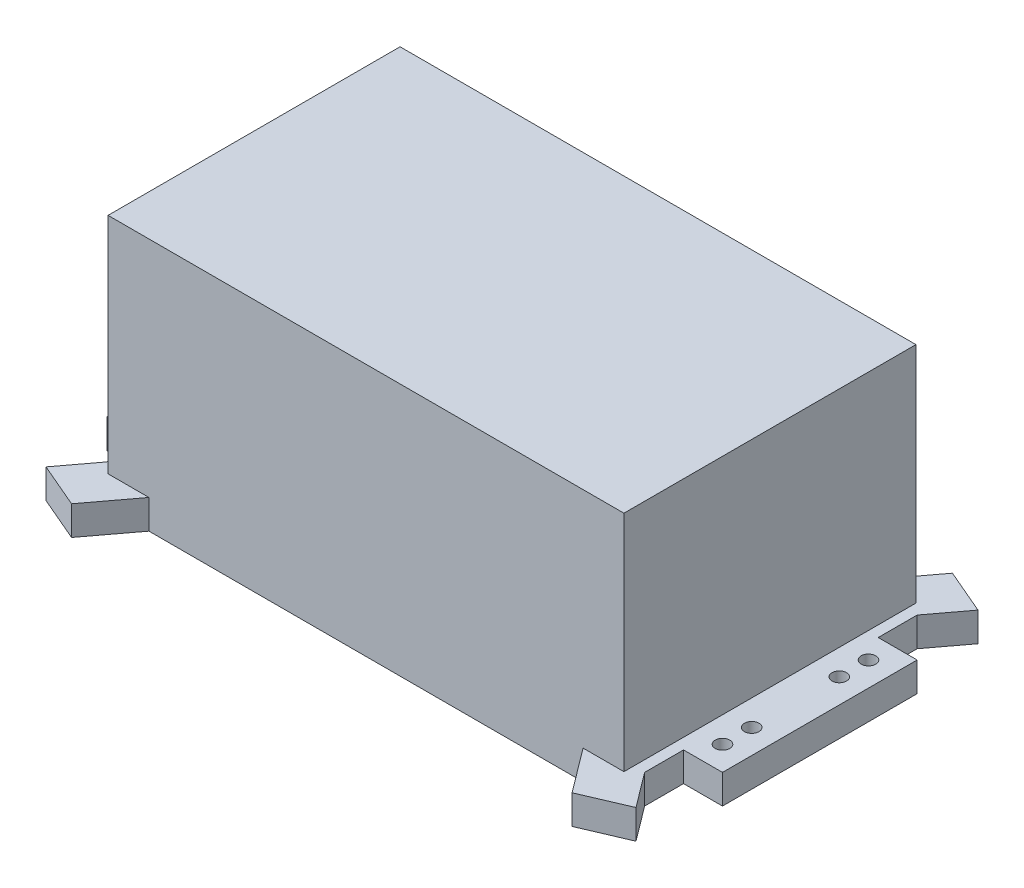
SolidWorks part; units mm, degrees
ref_plane "前视基准面" through (0, 0, 0) normal (0, 0, 1) x (1, 0, 0)
ref_plane "上视基准面" through (0, 0, 0) normal (0, 1, 0) x (1, 0, 0)
ref_plane "右视基准面" through (0, 0, 0) normal (1, 0, 0) x (0, 0, -1)
sketch "草图1" plane through (0, 0, 0) normal (0, 1, 0) x (1, 0, 0)
  line L0 (-65.7171, 0) -> (87.7991, 0) construction
  line L1 (44.6018, -30) -> (-44.6018, -30)
  line L3 (44.6018, 30) -> (-44.6018, 30)
  line L5 (53, -30) -> (-53, 30) construction
  line L6 (53, 30) -> (-53, -30) construction
  line L8 (63.25, -20) -> (63.25, 20)
  line L10 (-63.25, -20) -> (-63.25, 20)
  line L11 (63.25, 20) -> (55.25, 20)
  line L12 (55.25, 20) -> (55.25, 28)
  line L13 (55.25, 28) -> (60.6154, 35.1388)
  line L14 (60.6154, 35.1388) -> (51.4231, 39.0759)
  line L15 (51.4231, 39.0759) -> (44.6018, 30)
  line L16 (63.25, -20) -> (55.25, -20)
  line L17 (55.25, -20) -> (55.25, -28)
  line L18 (55.25, -28) -> (60.6154, -35.1388)
  line L19 (60.6154, -35.1388) -> (51.4231, -39.0759)
  line L20 (51.4231, -39.0759) -> (44.6018, -30)
  line L21 (0, -33.7082) -> (0, 42.5182) construction
  line L22 (-51.4231, -39.0759) -> (-44.6018, -30)
  line L23 (-60.6154, -35.1388) -> (-51.4231, -39.0759)
  line L24 (-55.25, -28) -> (-60.6154, -35.1388)
  line L25 (-55.25, -20) -> (-55.25, -28)
  line L26 (-63.25, -20) -> (-55.25, -20)
  line L27 (-63.25, 20) -> (-55.25, 20)
  line L28 (-55.25, 20) -> (-55.25, 28)
  line L29 (-55.25, 28) -> (-60.6154, 35.1388)
  line L30 (-51.4231, 39.0759) -> (-44.6018, 30)
  line L31 (-60.6154, 35.1388) -> (-51.4231, 39.0759)
  circle A0 centre (58.25, 15) radius 1.5
  circle A1 centre (-58.25, 15) radius 1.5
  circle A2 centre (58.25, 9) radius 1.5
  circle A3 centre (-58.25, 9) radius 1.5
  circle A4 centre (58.25, -9) radius 1.5
  circle A5 centre (58.25, -15) radius 1.5
  circle A6 centre (-58.25, -9) radius 1.5
  circle A7 centre (-58.25, -15) radius 1.5
  point P0 (0, 0)
  point P5 (0, 0)
  dimension "D5" = 3
  dimension "D6" = 3
  dimension "D7" = 3
  dimension "D8" = 3
  dimension "D1" = 60
  dimension "D2" = 106
  dimension "D3" = 40
  dimension "D4" = 126.5
  dimension "D9" = 8
  dimension "D10" = 8
  dimension "D11" = 10
extrude "凸台-拉伸1" add sketch "草图1" along normal blind 6
ref_plane "基准面1" through (0, 6, 0) normal (0, 1, 0) x (1, 0, 0)
sketch "草图2" plane through (0, 6, 0) normal (0, 1, 0) x (1, 0, 0)
  line L1 (53, -30) -> (-53, -30)
  line L2 (53, -30) -> (53, 30)
  line L3 (53, 30) -> (-53, 30)
  line L4 (-53, -30) -> (-53, 30)
  line L5 (53, -30) -> (-53, 30) construction
  line L6 (53, 30) -> (-53, -30) construction
  point P0 (0, 0)
  dimension "D1" = 60
  dimension "D2" = 106
extrude "凸台-拉伸2" add sketch "草图2" along normal blind 46
